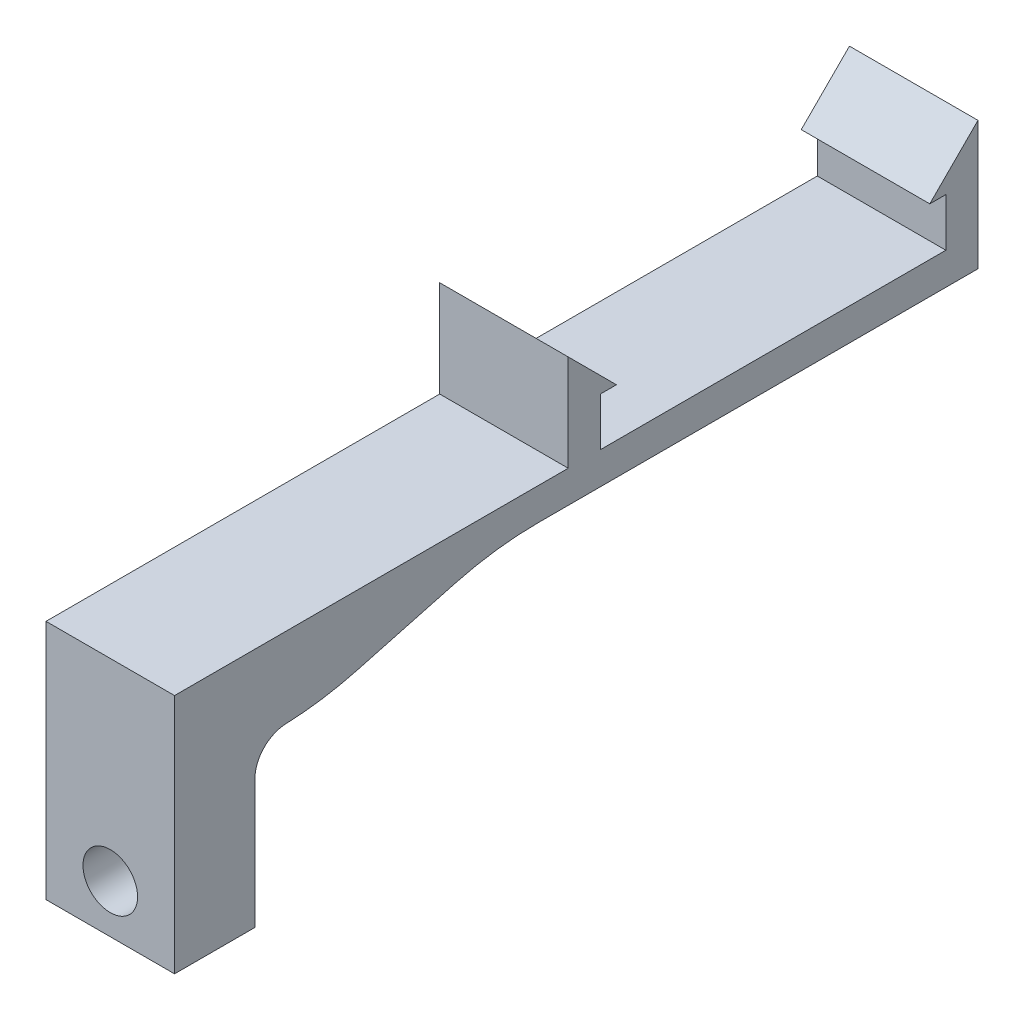
SolidWorks part; units mm, degrees
ref_plane "正面" through (0, 0, 0) normal (0, 0, 1) x (1, 0, 0)
ref_plane "平面" through (0, 0, 0) normal (0, 1, 0) x (1, 0, 0)
ref_plane "右側面" through (0, 0, 0) normal (1, 0, 0) x (0, 0, -1)
sketch "ｽｹｯﾁ1" plane through (0, 0, 0) normal (0, 0, 1) x (1, 0, 0)
  line L1 (-4, 7.5) -> (4, 7.5)
  line L2 (-4, 7.5) -> (-4, -7.5)
  line L3 (-4, -7.5) -> (4, -7.5)
  line L4 (4, 7.5) -> (4, -7.5)
  line L5 (-4, 7.5) -> (4, -7.5) construction
  line L6 (-4, -7.5) -> (4, 7.5) construction
  point P0 (0, 0)
  dimension "D1" = 15
  dimension "D2" = 8
extrude "ﾎﾞｽ - 押し出し1" add sketch "ｽｹｯﾁ1" along normal blind 5
sketch "ｽｹｯﾁ2" plane through (0, 0, 0) normal (0, 0, -1) x (-1, 0, 0)
  line L0 (4, 7.5) -> (4, -7.5) construction
  line L1 (-4, 7.5) -> (4, 7.5)
  line L2 (-4, 7.5) -> (-4, 2.5)
  line L3 (-4, 2.5) -> (4, 2.5)
  line L4 (4, 7.5) -> (4, 2.5)
  dimension "D1" = 5
extrude "ﾎﾞｽ - 押し出し2" add sketch "ｽｹｯﾁ2" along normal blind 45
sketch "ｽｹｯﾁ4" plane through (-4, 0, 0) normal (-1, 0, 0) x (0, 0, 1)
  line L0 (-45, 7.5) -> (-45, 13.5)
  line L1 (-45, 13.5) -> (-42, 10.5)
  line L2 (-42, 10.5) -> (-43, 10.5)
  line L4 (5, 7.5) -> (-45, 7.5) construction
  line L5 (-43, 7.5) -> (-45, 7.5)
  line L6 (-43, 10.5) -> (-43, 7.5)
  line L9 (-21.5, 7.5) -> (-21.5, 10.5)
  line L10 (-21.5, 10.5) -> (-22.5, 10.5)
  line L11 (-22.5, 10.5) -> (-19.5, 13.5)
  line L12 (-19.5, 13.5) -> (-19.5, 7.5)
  line L13 (-19.5, 7.5) -> (-21.5, 7.5)
  dimension "D1" = 45
  dimension "D2" = 2
  dimension "D3" = 1
  dimension "D4" = 3
  dimension "D5" = 21.5
extrude "ﾎﾞｽ - 押し出し3" add sketch "ｽｹｯﾁ4" against normal up to surface (8 mm away) up to face at (4, 0.8333, -13.3333)
sketch "ｽｹｯﾁ5" plane through (-4, 0, 0) normal (-1, 0, 0) x (0, 0, 1)
  line L0 (-45, 2.5) -> (-45, 5.5)
  line L1 (-45, 2.5) -> (-45, 13.5) construction
  line L2 (-45, 5.5) -> (-15, 5.5)
  line L3 (-15, 5.5) -> (-3.8038, 2.5)
  line L4 (-45, 2.5) -> (0, 2.5) construction
  line L5 (-3.8038, 2.5) -> (-45, 2.5)
  line L6 (5, 7.5) -> (-19.5, 7.5) construction
  dimension "D1" = 15
  dimension "D2" = 2
  dimension "D3" = 30
extrude "ｶｯﾄ - 押し出し1" cut sketch "ｽｹｯﾁ5" against normal through all
fillet "ﾌｨﾚｯﾄ1" radius 20 2 edges at (0, 2.5, -3.8038) (0, 5.5, -15)
fillet "ﾌｨﾚｯﾄ2" radius 2 1 edges at (0, 2.5, 0)
hole_wizard "M3 すきま穴1" positions "ｽｹｯﾁ6" profile "ｽｹｯﾁ7" hole size "M3" standard "JIS" end condition through all
sketch "ｽｹｯﾁ6" plane through (0, 0, 5) normal (0, 0, 1) x (1, 0, 0)
  line L0 (-4, -7.5) -> (4, -7.5) construction
  point P0 (0, -4.5)
  point P5 (0, 0)
  point P7 (0, -7.5)
  dimension "D1" = 3
sketch "ｽｹｯﾁ7" plane through (0, -4.5, 5) normal (1, 0, 0) x (0, -1, 0)
  line L0 (0, 0) -> (0, 50)
  line L1 (0, 50) -> (1.7, 50)
  line L2 (1.7, 50) -> (1.7, 0)
  line L5 (1.7, 0) -> (0, 0)
  line L11 (0, -6.35) -> (0, 107.95) construction
  dimension "通し穴の直径" = 3.4
  dimension "通し穴の深さ" = 50
